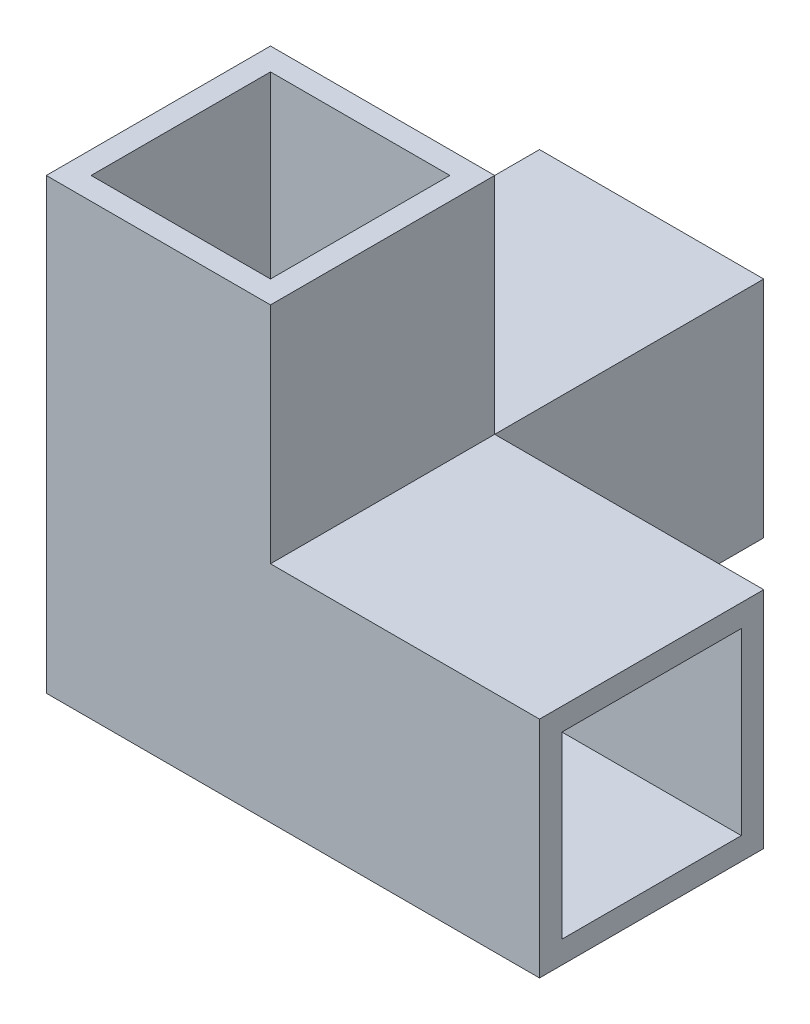
SolidWorks part; units mm, degrees
ref_plane "Front Plane" through (0, 0, 0) normal (0, 0, 1) x (1, 0, 0)
ref_plane "Top Plane" through (0, 0, 0) normal (0, 1, 0) x (1, 0, 0)
ref_plane "Right Plane" through (0, 0, 0) normal (1, 0, 0) x (0, 0, -1)
sketch "Sketch2" plane through (0, 0, 0) normal (0, 1, 0) x (1, 0, 0)
  line L0 (0, 0) -> (30, 0)
  line L1 (30, 0) -> (30, -25)
  line L2 (30, -25) -> (-25, -25)
  line L3 (-25, -25) -> (-25, 30)
  line L4 (-25, 30) -> (0, 30)
  line L5 (0, 30) -> (0, 0)
  dimension "D1" = 25
  dimension "D2" = 25
  dimension "D3" = 30
  dimension "D4" = 30
extrude "Boss-Extrude1" add sketch "Sketch2" along normal blind 25
sketch "Sketch3" plane through (0, 25, 0) normal (0, 1, 0) x (1, 0, 0)
  line L1 (-25, -25) -> (0, -25)
  line L2 (-25, -25) -> (-25, 0)
  line L3 (-25, 0) -> (0, 0)
  line L4 (0, -25) -> (0, 0)
extrude "Boss-Extrude2" add sketch "Sketch3" along normal blind 25
shell "Shell2" thickness 2.5
